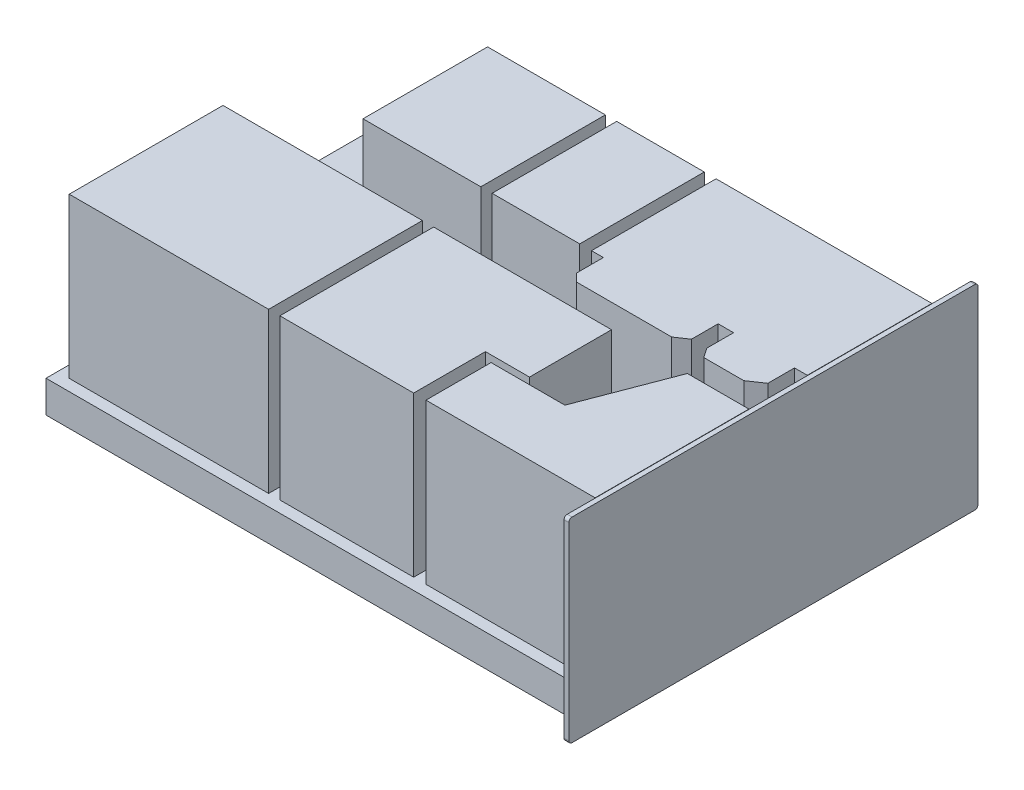
SolidWorks part; units mm, degrees
ref_plane "Front Plane" through (0, 0, 0) normal (0, 0, 1) x (1, 0, 0)
ref_plane "Top Plane" through (0, 0, 0) normal (0, 1, 0) x (1, 0, 0)
ref_plane "Right Plane" through (0, 0, 0) normal (1, 0, 0) x (0, 0, -1)
sketch "Sketch1" plane through (0, 0, 0) normal (0, 1, 0) x (1, 0, 0)
  line L1 (0, 0) -> (16.9901, 0)
  line L2 (0, 0) -> (0, -11.3267)
  line L3 (0, -11.3267) -> (16.9901, -11.3267)
  line L4 (16.9901, 0) -> (16.9901, -11.3267)
  point P5 (14.9217, -6.6486)
  point P6 (0, 0)
  point P7 (18.6945, -9.5591)
  point P8 (26.0247, -15.7035)
  point P9 (32.6541, -16.2425)
  point P10 (44.5656, -22.7641)
  point P11 (73.9917, -35.7576)
  point P12 (107.5092, -55.4736)
  point P13 (198.3964, -108.3709)
  point P14 (231.5496, -114.3749)
  point P15 (390.4574, -189.0616)
extrude "Boss-Extrude1" add sketch "Sketch1" along normal blind 1
sketch "Sketch2" plane through (16.9901, 0, 0) normal (1, 0, 0) x (0, 0, -1)
  line L1 (-12.0767, 0) -> (0.75, 0)
  line L2 (-12.0767, 0) -> (-12.0767, 6.1267)
  line L3 (-12.0767, 6.1267) -> (0.75, 6.1267)
  line L4 (0.75, 0) -> (0.75, 6.1267)
extrude "Boss-Extrude2" add sketch "Sketch2" along normal blind 0.15
fillet "Fillet2" radius 0.1 4 edges at (17.0651, 6.1267, -0.75) (17.0651, 0, -0.75) (17.0651, 0, 12.0767) (17.0651, 6.1267, 12.0767)
sketch "Sketch3" plane through (0, 1, 0) normal (0, 1, 0) x (1, 0, 0)
  line L0 (6.9713, -6.1454) -> (12.5469, -6.1454)
  line L1 (6.6178, -6.1454) -> (0.3672, -6.1454)
  line L2 (6.6178, -6.1454) -> (6.6178, -10.9659)
  line L3 (6.6178, -10.9659) -> (0.3672, -10.9659)
  line L4 (0.3672, -6.1454) -> (0.3672, -10.9659)
  line L5 (12.5469, -6.1454) -> (12.5469, -8.7163)
  line L6 (12.5469, -8.7163) -> (11.1651, -8.7163)
  line L7 (11.1651, -8.7163) -> (11.1651, -10.9659)
  line L8 (11.1651, -10.9659) -> (6.9713, -10.9659)
  line L9 (6.9713, -10.9659) -> (6.9713, -6.1454)
  line L10 (16.8532, -6.1454) -> (14.925, -6.1454)
  line L11 (14.925, -6.1454) -> (13.8645, -8.9252)
  line L12 (13.8645, -8.9252) -> (11.5507, -8.9252)
  line L13 (11.5507, -8.9252) -> (11.5507, -10.9659)
  line L14 (11.5507, -10.9659) -> (16.8532, -10.9659)
  line L15 (16.8532, -10.9659) -> (16.8532, -6.1454)
  line L16 (16.8532, -0.4091) -> (16.8532, -4.3136)
  line L17 (16.8532, -4.3136) -> (16.4515, -4.3136)
  line L18 (16.4515, -4.3136) -> (16.4515, -5.1492)
  line L19 (16.4515, -5.1492) -> (16.0016, -5.4545)
  line L20 (16.0016, -5.4545) -> (14.7483, -5.4545)
  line L21 (14.7483, -5.4545) -> (14.5411, -5.1492)
  line L22 (14.5411, -5.1492) -> (14.5411, -4.3136)
  line L23 (14.5411, -4.3136) -> (14.0574, -4.3136)
  line L24 (14.0574, -4.3136) -> (14.0574, -5.1492)
  line L25 (14.0574, -5.1492) -> (13.6888, -5.3993)
  line L26 (13.6888, -5.3993) -> (12.1452, -5.3993)
  line L27 (12.1452, -5.3993) -> (10.7099, -5.3993)
  line L28 (10.7099, -5.3993) -> (10.4598, -5.1492)
  line L29 (10.4598, -5.1492) -> (10.4598, -4.3136)
  line L30 (10.4598, -4.3136) -> (10.088, -4.3136)
  line L31 (10.088, -4.3136) -> (10.088, -0.4091)
  line L32 (10.088, -0.4091) -> (16.8532, -0.4091)
  line L33 (9.7181, -0.4091) -> (9.7181, -4.3136)
  line L34 (9.7181, -4.3136) -> (6.9713, -4.3136)
  line L35 (6.9713, -4.3136) -> (6.9713, -0.4091)
  line L36 (6.9713, -0.4091) -> (9.7181, -0.4091)
  line L37 (6.6178, -4.3136) -> (2.925, -4.3136)
  line L38 (2.925, -4.3136) -> (2.925, -0.4091)
  line L39 (2.925, -0.4091) -> (6.6178, -0.4091)
  line L40 (6.6178, -0.4091) -> (6.6178, -4.3136)
extrude "Boss-Extrude3" add sketch "Sketch3" along normal blind 5
sketch "Sketch4" plane through (0, 1, 0) normal (0, 1, 0) x (1, 0, 0)
  line L0 (0.3672, -4.3136) -> (0.3672, -0.4091)
  line L1 (0.3672, -0.4091) -> (1.6366, -0.4091)
  line L2 (1.6366, -0.4091) -> (2.665, -1.4374)
  line L3 (2.665, -1.4374) -> (2.665, -4.3136)
  line L4 (2.665, -4.3136) -> (0.3672, -4.3136)
extrude "Boss-Extrude4" add sketch "Sketch4" along normal blind 2
